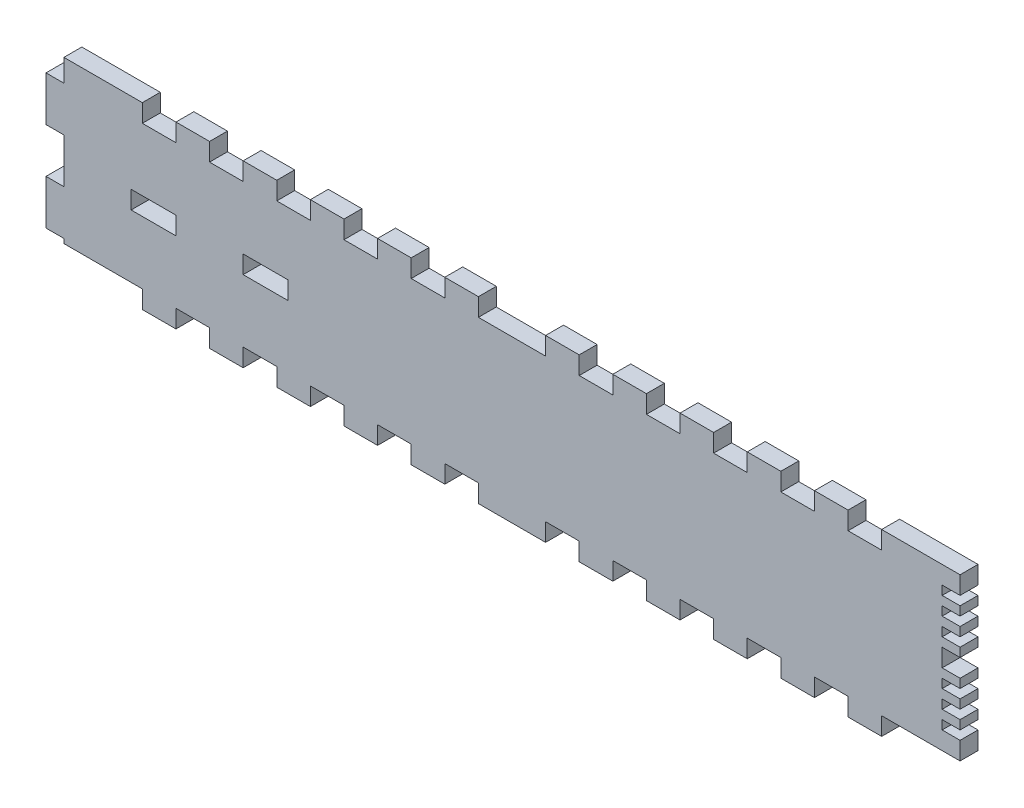
SolidWorks part; units mm, degrees
ref_plane "Plan de face" through (0, 0, 0) normal (0, 0, 1) x (1, 0, 0)
ref_plane "Plan de dessus" through (0, 0, 0) normal (0, 1, 0) x (1, 0, 0)
ref_plane "Plan de droite" through (0, 0, 0) normal (1, 0, 0) x (0, 0, -1)
sketch "Esquisse1" plane through (0, 0, 0) normal (0, 0, 1) x (1, 0, 0)
  line L1 (-200, -40) -> (200, -40)
  line L2 (-200, -40) -> (-200, 40)
  line L3 (-200, 40) -> (200, 40)
  line L4 (200, -40) -> (200, 40)
  line L5 (-200, -40) -> (200, 40) construction
  line L6 (-200, 40) -> (200, -40) construction
  point P0 (0, 0)
  dimension "D1" = 400
  dimension "D2" = 80
extrude "Boss.-Extru.1" add sketch "Esquisse1" along normal blind 8
sketch "Esquisse2" plane through (0, 0, 0) normal (0, 0, 1) x (1, 0, 0)
  line L0 (-200, 40) -> (-200, -40) construction
  line L1 (-200, 10) -> (-208, 10)
  line L2 (-200, 10) -> (-200, 30)
  line L3 (-200, 30) -> (-208, 30)
  line L4 (-208, 10) -> (-208, 30)
  line L5 (-200, 0) -> (-152.7974, 0) construction
  line L6 (-200, -30) -> (-208, -30)
  line L7 (-208, -10) -> (-208, -30)
  line L8 (-200, -10) -> (-208, -10)
  line L9 (-200, -10) -> (-200, -30)
  point P6 (-200, 0)
  dimension "D1" = 10
  dimension "D2" = 20
  dimension "D3" = 8
extrude "Boss.-Extru.2" add sketch "Esquisse2" along normal blind 8
sketch "Esquisse4" plane through (0, 0, 0) normal (0, 0, 1) x (1, 0, 0)
  line L0 (200, 40) -> (-200, 40) construction
  line L1 (0, 40) -> (-15, 40)
  line L3 (0, 32) -> (-15, 32)
  line L4 (-15, 40) -> (-15, 32)
  line L5 (-30, 40) -> (-30, 32)
  line L6 (-30, 40) -> (-45, 40)
  line L7 (-45, 40) -> (-45, 32)
  line L8 (-30, 32) -> (-45, 32)
  line L9 (-60, 40) -> (-60, 32)
  line L10 (-60, 40) -> (-75, 40)
  line L11 (-75, 40) -> (-75, 32)
  line L12 (-60, 32) -> (-75, 32)
  line L13 (-90, 40) -> (-90, 32)
  line L14 (-90, 40) -> (-105, 40)
  line L15 (-105, 40) -> (-105, 32)
  line L16 (-90, 32) -> (-105, 32)
  line L17 (-120, 40) -> (-120, 32)
  line L18 (-120, 40) -> (-135, 40)
  line L19 (-135, 40) -> (-135, 32)
  line L20 (-120, 32) -> (-135, 32)
  line L21 (-150, 40) -> (-150, 32)
  line L22 (-150, 40) -> (-165, 40)
  line L23 (-165, 40) -> (-165, 32)
  line L24 (-150, 32) -> (-165, 32)
  line L25 (0, 0) -> (0, 21.1046) construction
  line L26 (30, 40) -> (45, 40)
  line L27 (45, 40) -> (45, 32)
  line L28 (30, 32) -> (45, 32)
  line L29 (30, 40) -> (30, 32)
  line L30 (60, 40) -> (75, 40)
  line L31 (75, 40) -> (75, 32)
  line L32 (60, 32) -> (75, 32)
  line L33 (60, 40) -> (60, 32)
  line L34 (90, 40) -> (105, 40)
  line L35 (105, 40) -> (105, 32)
  line L36 (90, 32) -> (105, 32)
  line L37 (90, 40) -> (90, 32)
  line L38 (120, 40) -> (135, 40)
  line L39 (135, 40) -> (135, 32)
  line L40 (120, 32) -> (135, 32)
  line L41 (120, 40) -> (120, 32)
  line L42 (150, 40) -> (165, 40)
  line L43 (165, 40) -> (165, 32)
  line L44 (150, 32) -> (165, 32)
  line L45 (150, 40) -> (150, 32)
  line L47 (0, 40) -> (15, 40)
  line L49 (0, 32) -> (15, 32)
  line L50 (15, 40) -> (15, 32)
  dimension "D1" = 15
  dimension "D2" = 8
  dimension "D4" = 15
  dimension "D3" = 6
extrude "Enlèv. mat.-Extru.1" cut sketch "Esquisse4" along normal through all
sketch "Esquisse5" plane through (0, 0, 0) normal (0, 0, 1) x (1, 0, 0)
  line L0 (-200, -40) -> (200, -40) construction
  line L1 (-15, -40) -> (-30, -40)
  line L2 (-15, -40) -> (-15, -32)
  line L3 (-15, -32) -> (-30, -32)
  line L4 (-30, -40) -> (-30, -32)
  line L5 (-45, -40) -> (-45, -32)
  line L6 (-45, -40) -> (-60, -40)
  line L7 (-60, -40) -> (-60, -32)
  line L8 (-45, -32) -> (-60, -32)
  line L9 (-75, -40) -> (-75, -32)
  line L10 (-75, -40) -> (-90, -40)
  line L11 (-90, -40) -> (-90, -32)
  line L12 (-75, -32) -> (-90, -32)
  line L13 (-105, -40) -> (-105, -32)
  line L14 (-105, -40) -> (-120, -40)
  line L15 (-120, -40) -> (-120, -32)
  line L16 (-105, -32) -> (-120, -32)
  line L17 (-135, -40) -> (-135, -32)
  line L18 (-135, -40) -> (-150, -40)
  line L19 (-150, -40) -> (-150, -32)
  line L20 (-135, -32) -> (-150, -32)
  line L22 (0, 0) -> (0, -22.7254) construction
  line L23 (-200, -40) -> (-165, -40)
  line L24 (-200, -40) -> (-200, -32)
  line L25 (-200, -32) -> (-165, -32)
  line L26 (-165, -40) -> (-165, -32)
  line L27 (15, -32) -> (30, -32)
  line L28 (30, -40) -> (30, -32)
  line L29 (15, -40) -> (30, -40)
  line L30 (15, -40) -> (15, -32)
  line L31 (45, -40) -> (60, -40)
  line L32 (60, -40) -> (60, -32)
  line L33 (45, -32) -> (60, -32)
  line L34 (45, -40) -> (45, -32)
  line L35 (75, -40) -> (90, -40)
  line L36 (90, -40) -> (90, -32)
  line L37 (75, -32) -> (90, -32)
  line L38 (75, -40) -> (75, -32)
  line L39 (105, -40) -> (120, -40)
  line L40 (120, -40) -> (120, -32)
  line L41 (105, -32) -> (120, -32)
  line L42 (105, -40) -> (105, -32)
  line L43 (135, -40) -> (150, -40)
  line L44 (150, -40) -> (150, -32)
  line L45 (135, -32) -> (150, -32)
  line L46 (135, -40) -> (135, -32)
  line L47 (200, -32) -> (165, -32)
  line L48 (165, -40) -> (165, -32)
  line L49 (200, -40) -> (165, -40)
  line L50 (200, -40) -> (200, -32)
  point P6 (0, -40)
  dimension "D1" = 15
  dimension "D2" = 8
  dimension "D3" = 15
  dimension "D5" = 35
  dimension "D6" = 8
  dimension "D4" = 5
extrude "Enlèv. mat.-Extru.2" cut sketch "Esquisse5" along normal through all
sketch "Esquisse6" plane through (0, 0, 0) normal (0, 0, 1) x (1, 0, 0)
  line L0 (-200, 10) -> (-200, -10) construction
  line L1 (-170, -4) -> (-150, -4)
  line L2 (-170, -4) -> (-170, 4)
  line L3 (-170, 4) -> (-150, 4)
  line L4 (-150, -4) -> (-150, 4)
  line L5 (-170, -4) -> (-150, 4) construction
  line L6 (-170, 4) -> (-150, -4) construction
  line L7 (-120, -4) -> (-120, 4)
  line L8 (-120, -4) -> (-100, -4)
  line L9 (-100, -4) -> (-100, 4)
  line L10 (-120, 4) -> (-100, 4)
  point P0 (-160, 0)
  point P7 (-200, 0)
  dimension "D1" = 30
  dimension "D2" = 20
  dimension "D3" = 8
  dimension "D4" = 2
extrude "Enlèv. mat.-Extru.3" cut sketch "Esquisse6" along normal through all
sketch "Esquisse8" plane through (0, 0, 0) normal (0, 0, 1) x (1, 0, 0)
  line L0 (200, -32) -> (200, 40) construction
  line L2 (200, 4) -> (200, 8)
  line L3 (200, 8) -> (192, 8)
  line L4 (192, 4) -> (192, 8)
  line L5 (200, 12) -> (200, 16)
  line L6 (200, 12) -> (192, 12)
  line L7 (192, 12) -> (192, 16)
  line L8 (200, 16) -> (192, 16)
  line L9 (200, 20) -> (200, 24)
  line L10 (200, 20) -> (192, 20)
  line L11 (192, 20) -> (192, 24)
  line L12 (200, 24) -> (192, 24)
  line L13 (200, 28) -> (200, 32)
  line L14 (200, 28) -> (192, 28)
  line L15 (192, 28) -> (192, 32)
  line L16 (200, 32) -> (192, 32)
  line L17 (192, 4) -> (180.4823, 4) construction
  line L18 (200, -4) -> (192, -4)
  line L19 (192, -4) -> (192, -8)
  line L20 (200, -8) -> (192, -8)
  line L21 (200, -4) -> (200, -8)
  line L22 (200, -12) -> (192, -12)
  line L23 (192, -12) -> (192, -16)
  line L24 (200, -16) -> (192, -16)
  line L25 (200, -12) -> (200, -16)
  line L26 (200, -20) -> (192, -20)
  line L27 (192, -20) -> (192, -24)
  line L28 (200, -24) -> (192, -24)
  line L29 (200, -20) -> (200, -24)
  line L32 (200, 4) -> (200, 0)
  line L33 (200, 0) -> (192, 0)
  line L34 (192, 4) -> (192, 0)
  dimension "D1" = 8
  dimension "D2" = 4
  dimension "D4" = 4
  dimension "D3" = 4
extrude "Enlèv. mat.-Extru.5" cut sketch "Esquisse8" along normal through all
